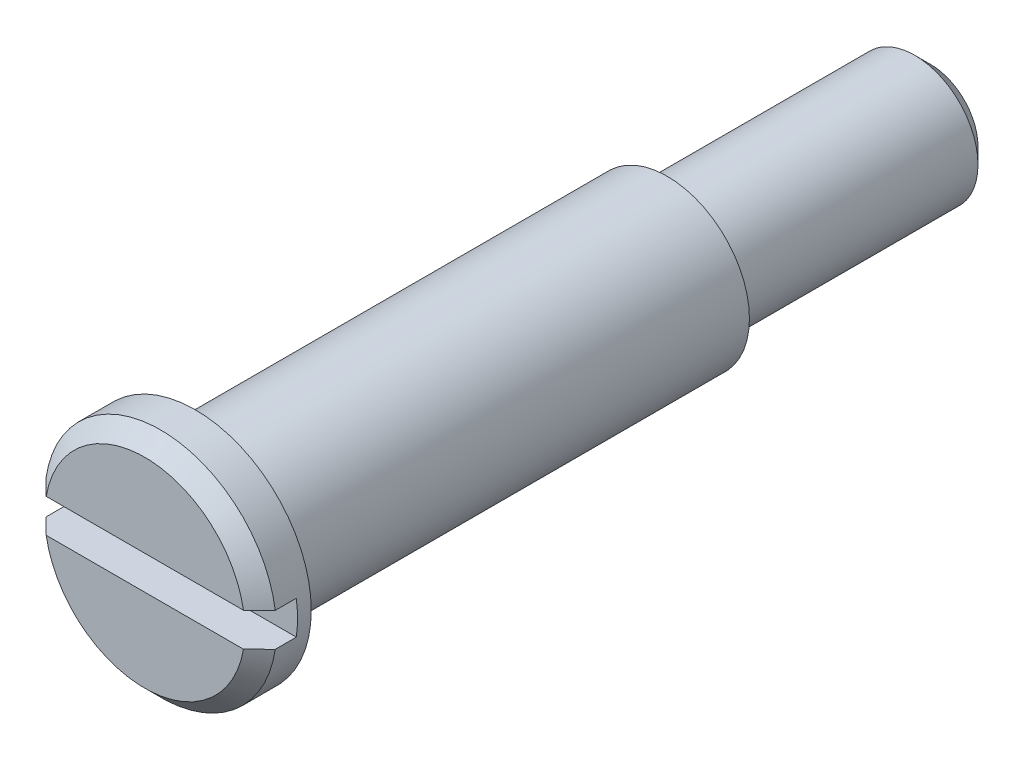
SolidWorks part; units mm, degrees
ref_plane "Front Plane" through (0, 0, 0) normal (0, 0, 1) x (1, 0, 0)
ref_plane "Top Plane" through (0, 0, 0) normal (0, 1, 0) x (1, 0, 0)
ref_plane "Right Plane" through (0, 0, 0) normal (1, 0, 0) x (0, 0, -1)
sketch "Sketch1" plane through (0, 0, 0) normal (0, 0, 1) x (1, 0, 0)
  circle A0 centre (0, 0) radius 3.9
  dimension "D1" = 7.8
extrude "Extrude1" add sketch "Sketch1" against normal blind 22.4
sketch "Sketch2" plane through (0, 0, -22.4) normal (0, 0, -1) x (-1, 0, 0)
  circle A0 centre (0, 0) radius 3
  dimension "D1" = 6
extrude "Extrude2" add sketch "Sketch2" along normal blind 12.5
cosmetic thread "Cosmetic Thread1" parameters "D2"=4.7
sketch "Sketch3" plane through (0, 0, 0) normal (0, 0, 1) x (1, 0, 0)
  circle A0 centre (0, 0) radius 5.5
  dimension "D1" = 11
extrude "Extrude3" add sketch "Sketch3" along normal blind 2.4
chamfer "Chamfer1" distance 0.75 angle 45 1 edges at (-3, 0, -34.9)
sketch "Sketch4" plane through (0, 0, 2.4) normal (0, 0, 1) x (1, 0, 0)
  line L0 (-5.5, 0) -> (5.5, 0) construction
  line L1 (-5.5, 0.8) -> (5.5, 0.8)
  line L2 (-5.5, 0.8) -> (-5.5, -0.8)
  line L3 (-5.5, -0.8) -> (5.5, -0.8)
  line L4 (5.5, 0.8) -> (5.5, -0.8)
  circle A1 centre (0, 0) radius 5.5 construction
  dimension "D1" = 1.6
extrude "Cut-Extrude1" cut sketch "Sketch4" against normal blind 1.75
chamfer "Chamfer2" distance 0.75 angle 45 2 edges at (0, -5.5, 2.4) (0, 5.5, 2.4)
